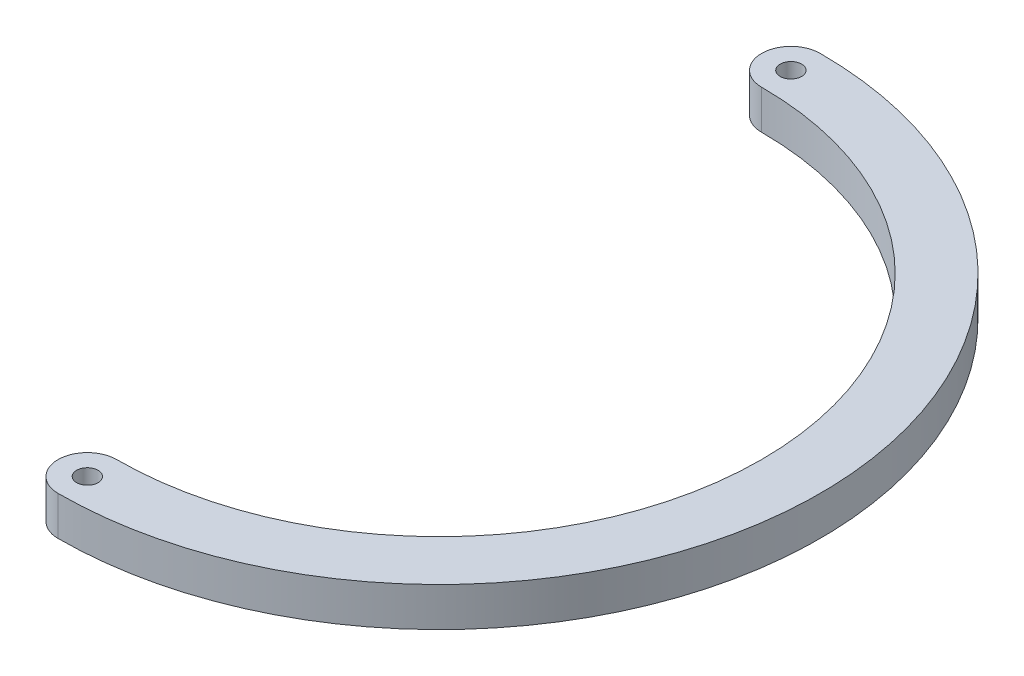
SolidWorks part; units mm, degrees
ref_plane "Front Plane" through (0, 0, 0) normal (0, 0, 1) x (1, 0, 0)
ref_plane "Top Plane" through (0, 0, 0) normal (0, 1, 0) x (1, 0, 0)
ref_plane "Right Plane" through (0, 0, 0) normal (1, 0, 0) x (0, 0, -1)
sketch "Sketch1" plane through (0, 0, 0) normal (0, 1, 0) x (1, 0, 0)
  line L0 (0, 97.55) -> (0, -97.55) construction
  line L1 (40.2045, 110.4609) -> (0, 0) construction
  line L2 (115.7642, 20.4123) -> (0, 0) construction
  line L3 (-1000, 0) -> (49000, 0) construction
  line L4 (0, 0) -> (90.0485, 75.5597) construction
  line L5 (56.4433, 88.5983) -> (0, 0) construction
  arc A0 (0, -82.55) -> (0, 82.55) centre (0, 0) ccw
  arc A1 (0, -97.55) -> (96.068, 16.9394) centre (0, 0) ccw
  circle A2 centre (0, 0) radius 97.55 construction
  circle A3 centre (0, 0) radius 82.55 construction
  arc A4 (0, 97.55) -> (0, 82.55) centre (0, 90.05) ccw
  arc A5 (0, -82.55) -> (0, -97.55) centre (0, -90.05) ccw
  circle A6 centre (0, 0) radius 117.55 construction
  circle A8 centre (0, 0) radius 105.05 construction
  arc A9 (33.3641, 91.667) -> (96.068, 16.9394) centre (0, 0) cw
  arc A14 (33.3641, 91.667) -> (0, 97.55) centre (0, 0) ccw
  point P12 (0, 90.05)
  point P13 (0, -90.05)
  dimension "D2" = 165.1
  dimension "D4" = 60
  dimension "D5" = 10
  dimension "D6" = 17.5
  dimension "D1" = 15
extrude "Boss-Extrude1" add sketch "Sketch1" along normal mid plane 10
hole_wizard "M5 Clearance Hole1" positions "Sketch2" profile "Sketch3" hole size "M5" standard "ANSI Metric" end condition through all
sketch "Sketch2" plane through (0, 5, 0) normal (0, 1, 0) x (1, 0, 0)
  point P0 (0, 90.05)
  point P3 (0, -90.05)
sketch "Sketch3" plane through (0, 5, -90.05) normal (1, 0, 0) x (0, 0, 1)
  line L0 (0, 0) -> (0, 10)
  line L1 (0, 10) -> (2.75, 10)
  line L2 (2.75, 10) -> (2.75, 0)
  line L5 (2.75, 0) -> (0, 0)
  line L11 (0, -6.35) -> (0, 107.95) construction
  dimension "Thru Hole Dia." = 5.5
  dimension "Thru Hole Depth" = 10
equation "\"D2@Sketch1\"=152.40 + (6.35*2)"
